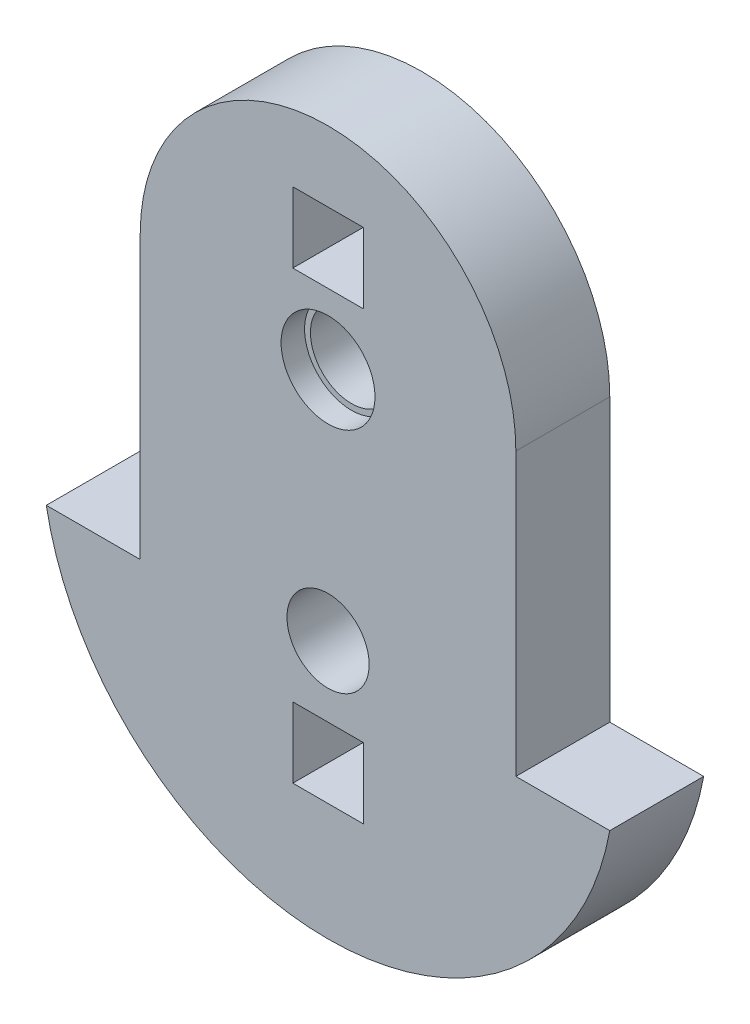
SolidWorks part; units mm, degrees
ref_plane "Front Plane" through (0, 0, 0) normal (0, 0, 1) x (1, 0, 0)
ref_plane "Top Plane" through (0, 0, 0) normal (0, 1, 0) x (1, 0, 0)
ref_plane "Right Plane" through (0, 0, 0) normal (1, 0, 0) x (0, 0, -1)
sketch "Sketch1" plane through (0, 0, 0) normal (0, 0, 1) x (1, 0, 0)
  line L0 (-8, 6) -> (-8, -6)
  line L3 (8, 6) -> (8, -6)
  line L4 (-8, 0) -> (8, 0) construction
  line L5 (0, 14) -> (0, -14) construction
  line L6 (-8, -6) -> (-12, -6)
  line L7 (-1.5, 8) -> (1.5, 8) construction
  line L8 (-1.5, 8) -> (-1.5, 11) construction
  line L9 (-1.5, 11) -> (1.5, 11) construction
  line L10 (1.5, 8) -> (1.5, 11) construction
  line L11 (-1.5, 8) -> (1.5, 11) construction
  line L12 (-1.5, 11) -> (1.5, 8) construction
  line L17 (-1.5, -11) -> (1.5, -11) construction
  line L19 (-1.5, -11) -> (-1.5, -8) construction
  line L20 (-1.5, -8) -> (1.5, -8) construction
  line L21 (1.5, -11) -> (1.5, -8) construction
  line L22 (-1.5, -11) -> (1.5, -8) construction
  line L23 (-1.5, -8) -> (1.5, -11) construction
  line L24 (8, -6) -> (12, -6)
  circle A2 centre (0, 5) radius 1.75
  circle A4 centre (0, -5) radius 4.5 construction
  circle A5 centre (0, -5) radius 1.75
  circle A6 centre (0, -5) radius 2 construction
  arc A9 (8, -6) -> (-8, -6) centre (0, -6) cw construction
  arc A10 (-8, 6) -> (8, 6) centre (0, 6) cw
  circle A11 centre (0, 5) radius 4.5 construction
  arc A13 (-12, -6) -> (12, -6) centre (0, -3.8) ccw
  point P9 (0, 0)
  point P18 (0, 0)
  point P19 (0, -0.5)
  point P21 (0, -9.5)
  point P25 (0, 9.5)
  point P31 (0, -9.5)
  dimension "D1" = 8
  dimension "D2" = 3.5
  dimension "D3" = 9
  dimension "D6" = 5
  dimension "D7" = 4
  dimension "D10" = 1.2
  dimension "D4" = 3
  dimension "D5" = 12
  dimension "D8" = 5
  dimension "D9" = 4
extrude "Boss-Extrude1" add sketch "Sketch1" along normal blind 4
sketch "Sketch2" plane through (0, 0, 4) normal (0, 0, 1) x (1, 0, 0)
  line L0 (0, 5) -> (0, 9.5) construction
  line L1 (0, 5) -> (0, -6.75) construction
  line L2 (-1.5, 8) -> (1.5, 8)
  line L3 (-1.5, 8) -> (-1.5, 11)
  line L4 (-1.5, 11) -> (1.5, 11)
  line L5 (1.5, 8) -> (1.5, 11)
  line L6 (-1.5, 8) -> (1.5, 11) construction
  line L7 (-1.5, 11) -> (1.5, 8) construction
  line L8 (-1.75, -5) -> (1.75, -5) construction
  line L10 (-1.5, -11) -> (1.5, -11)
  line L11 (-1.5, -11) -> (-1.5, -8)
  line L12 (-1.5, -8) -> (1.5, -8)
  line L13 (1.5, -11) -> (1.5, -8)
  line L14 (-1.5, -11) -> (1.5, -8) construction
  line L15 (-1.5, -8) -> (1.5, -11) construction
  circle A0 centre (0, 5) radius 4.5 construction
  circle A1 centre (0, -5) radius 1.75 construction
  circle A2 centre (0, -5) radius 4.5 construction
  point P17 (0, -9.5)
  dimension "D1" = 10
  dimension "D4" = 9
  dimension "D2" = 3
  dimension "D3" = 3
  dimension "D5" = 3
  dimension "D6" = 3
extrude "Cut-Extrude1" cut sketch "Sketch2" against normal through all
sketch "Sketch3" plane through (0, 0, 4) normal (0, 0, 1) x (1, 0, 0)
  circle A0 centre (0, 5) radius 2
  dimension "D1" = 4
extrude "Cut-Extrude2" cut sketch "Sketch3" against normal blind 1
